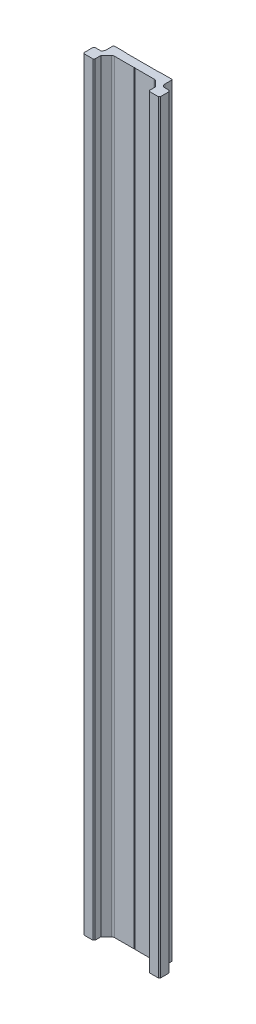
SolidWorks part; units mm, degrees
ref_plane "Front Plane" through (0, 0, 0) normal (0, 0, 1) x (1, 0, 0)
ref_plane "Top Plane" through (0, 0, 0) normal (0, 1, 0) x (1, 0, 0)
ref_plane "Right Plane" through (0, 0, 0) normal (1, 0, 0) x (0, 0, -1)
ref_plane "Plane1" through (0, 200, 0) normal (0, 1, 0) x (1, 0, 0)
sketch "Sketch1" plane through (0, 200, 0) normal (0, 1, 0) x (1, 0, 0)
  line L0 (0, -3.8557) -> (0.25, -4)
  line L1 (0.25, -4) -> (9.0787, -4)
  line L2 (10.1394, -4.4394) -> (12.5, -6.8)
  line L3 (12.5, -6.8) -> (12.5, -9.5)
  line L4 (12.5, -9.5) -> (13, -10)
  line L5 (13, -10) -> (17, -10)
  line L6 (17, -10) -> (17.5, -9.5)
  line L7 (17.5, -9.5) -> (17.5, -5.5)
  line L8 (17.5, -5.5) -> (17, -5)
  line L9 (17, -5) -> (14.3, -5)
  line L10 (14.3, -5) -> (14.0858, -4.7858)
  line L11 (13.5, -3.3716) -> (13.5, -0.3)
  line L12 (13.5, -0.3) -> (13.2, 0)
  line L13 (13.2, 0) -> (7.5, 0)
  line L14 (7.5, 0) -> (7.4, -0.1)
  line L15 (7.4, -0.1) -> (-7.4, -0.1)
  line L16 (-7.4, -0.1) -> (-7.5, 0)
  line L17 (-7.5, 0) -> (-13.2, 0)
  line L18 (-13.2, 0) -> (-13.5, -0.3)
  line L19 (-13.5, -0.3) -> (-13.5, -3.3716)
  line L20 (-14.0858, -4.7858) -> (-14.3, -5)
  line L21 (-14.3, -5) -> (-17, -5)
  line L22 (-17, -5) -> (-17.5, -5.5)
  line L23 (-17.5, -5.5) -> (-17.5, -9.5)
  line L24 (-17.5, -9.5) -> (-17, -10)
  line L25 (-17, -10) -> (-13, -10)
  line L26 (-13, -10) -> (-12.5, -9.5)
  line L27 (-12.5, -9.5) -> (-12.5, -6.8)
  line L28 (-12.5, -6.8) -> (-10.1394, -4.4394)
  line L29 (-9.0787, -4) -> (-0.25, -4)
  line L30 (-0.25, -4) -> (0, -3.8557)
  arc A0 (9.0787, -4) -> (10.1394, -4.4394) centre (9.0787, -5.5) cw
  arc A1 (14.0858, -4.7858) -> (13.5, -3.3716) centre (15.5, -3.3716) cw
  arc A2 (-13.5, -3.3716) -> (-14.0858, -4.7858) centre (-15.5, -3.3716) cw
  arc A3 (-10.1394, -4.4394) -> (-9.0787, -4) centre (-9.0787, -5.5) cw
extrude "Boss-Extrude1" add sketch "Sketch1" against normal blind 350
ref_plane "Plane2" through (0, 210, 0) normal (0, 1, 0) x (1, 0, 0)
